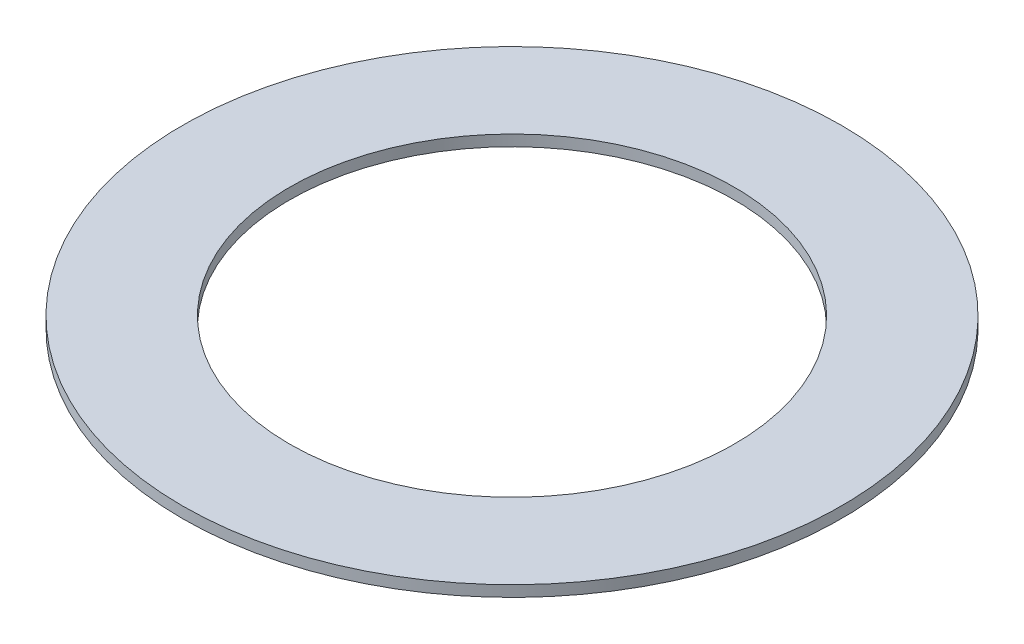
SolidWorks part; units mm, degrees
ref_plane "Front Plane" through (0, 0, 0) normal (0, 0, 1) x (1, 0, 0)
ref_plane "Top Plane" through (0, 0, 0) normal (0, 1, 0) x (1, 0, 0)
ref_plane "Right Plane" through (0, 0, 0) normal (1, 0, 0) x (0, 0, -1)
sketch "Sketch1" plane through (0, 0, 0) normal (0, 1, 0) x (1, 0, 0)
  circle A0 centre (0, 0) radius 20.15
  circle A1 centre (0, 0) radius 29.85
  dimension "D1" = 40.3
  dimension "D2" = 59.7
extrude "Boss-Extrude1" add sketch "Sketch1" along normal blind 1
